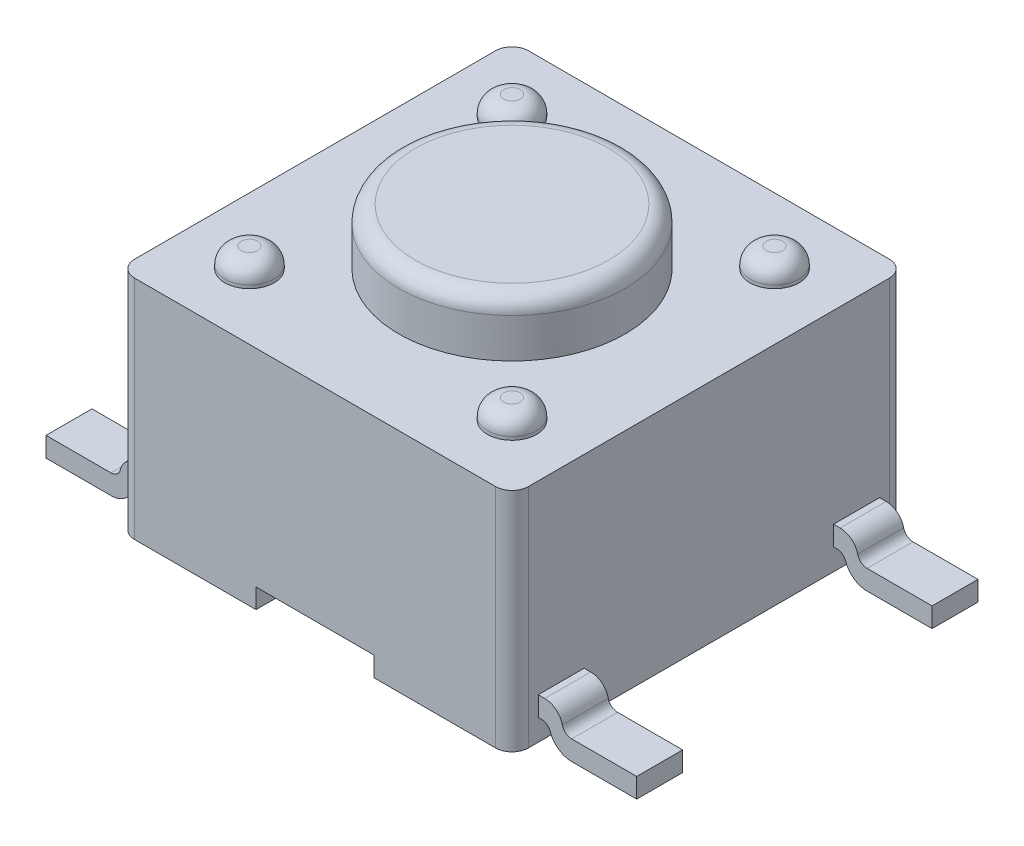
SolidWorks part; units mm, degrees
ref_plane "Front Plane" through (0, 0, 0) normal (0, 0, 1) x (1, 0, 0)
ref_plane "Top Plane" through (0, 0, 0) normal (0, 1, 0) x (1, 0, 0)
ref_plane "Right Plane" through (0, 0, 0) normal (1, 0, 0) x (0, 0, -1)
sketch "Sketch1" plane through (0, 0, 0) normal (0, 1, 0) x (1, 0, 0)
  line L1 (-3, -3) -> (3, -3)
  line L2 (-3, -3) -> (-3, 3)
  line L3 (-3, 3) -> (3, 3)
  line L4 (3, -3) -> (3, 3)
  line L5 (-3, -3) -> (3, 3) construction
  line L6 (-3, 3) -> (3, -3) construction
  point P0 (0, 0)
  dimension "D1" = 6
  dimension "D2" = 6
extrude "Boss-Extrude1" add sketch "Sketch1" along normal blind 3.45
sketch "Sketch2" plane through (0, 3.45, 0) normal (0, 1, 0) x (1, 0, 0)
  circle A0 centre (0, 0) radius 1.725
  dimension "D1" = 3.45
extrude "Boss-Extrude2" add sketch "Sketch2" along normal blind 4.3 from surface at -3.45 starting at plane "Top Plane"
sketch "Sketch3" plane through (0, 3.45, 0) normal (0, 1, 0) x (1, 0, 0)
  line L0 (-3, -3) -> (3, -3) construction
  line L1 (3, -3) -> (3, 3) construction
  circle A0 centre (2, -2) radius 0.375
  dimension "D3" = 0.75
  dimension "D1" = 1
  dimension "D2" = 1
extrude "Boss-Extrude3" add sketch "Sketch3" along normal blind 0.3 separate body
fillet "Fillet1" radius 0.25 1 edges at (2, 3.75, 2.375)
ref_plane "Plane1" through (0, 0, 2.25) normal (0, 0, 1) x (1, 0, 0)
sketch "Sketch4" plane through (0, 0, 2.25) normal (0, 0, 1) x (1, 0, 0)
  line L0 (-3, 0) -> (3, 0) construction
  line L1 (3.5093, 0) -> (4.5, 0)
  line L3 (3.5093, 0.3) -> (4.5, 0.3)
  line L4 (4.5, 0) -> (4.5, 0.3)
  line L5 (3, 0.6278) -> (3.1, 0.6278)
  line L6 (3, 3.45) -> (3, 0) construction
  line L7 (3, 0.3278) -> (3.0489, 0.3278)
  line L8 (3, 0.3278) -> (3, 0.6278)
  arc A0 (3.1, 0.6278) -> (3.3669, 0.4141) centre (3.1, 0.3543) cw
  arc A1 (3.3669, 0.4141) -> (3.5093, 0.3) centre (3.5093, 0.446) ccw
  arc A2 (3.0489, 0.3278) -> (3.1833, 0.2321) centre (3.0489, 0.1855) cw
  arc A3 (3.1833, 0.2321) -> (3.5093, 0) centre (3.5093, 0.345) ccw
  point P19 (3.189, 0.2102)
  point P20 (3.3669, 0.4141)
  dimension "D1" = 4.5
  dimension "D2" = 0.3
  dimension "D3" = 0.1
  dimension "D4" = 0.3
extrude "Boss-Extrude4" add sketch "Sketch4" along normal mid plane 0.7 separate body
mirror "Mirror3" about plane through (0, 0, 0) normal (1, 0, 0) of bodies 103 104
mirror "Mirror4" about plane through (0, 0, 0) normal (0, 0, 1) of bodies 109 108 104 103
sketch "Sketch5" plane through (0, 0, 3) normal (0, 0, 1) x (1, 0, 0)
  line L0 (-3, 0) -> (3, 0) construction
  line L1 (-0.9, 0) -> (0.9, 0)
  line L2 (-0.9, 0) -> (-0.9, 0.3)
  line L3 (-0.9, 0.3) -> (0.9, 0.3)
  line L4 (0.9, 0) -> (0.9, 0.3)
  point P6 (0, 0.3)
  dimension "D1" = 0.3
  dimension "D2" = 1.8
extrude "Cut-Extrude1" cut sketch "Sketch5" against normal through all
fillet "Fillet2" radius 0.25 4 edges at (3, 1.725, -3) (3, 1.725, 3) (-3, 1.725, -3) (-3, 1.725, 3)
fillet "Fillet3" radius 0.25 1 edges at (0, 4.3, 1.725)
